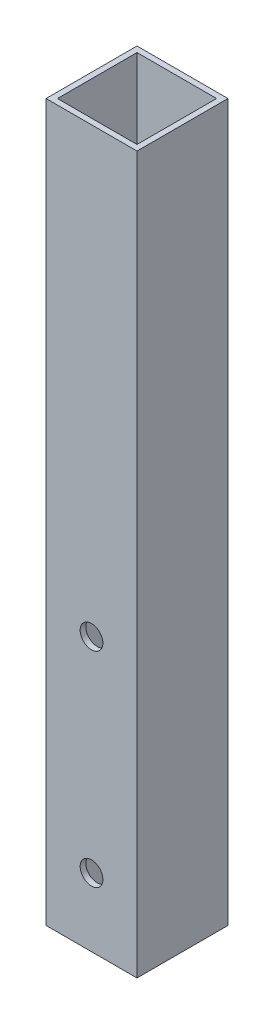
SolidWorks part; units mm, degrees
ref_plane "Front Plane" through (0, 0, 0) normal (0, 0, 1) x (1, 0, 0)
ref_plane "Top Plane" through (0, 0, 0) normal (0, 1, 0) x (1, 0, 0)
ref_plane "Right Plane" through (0, 0, 0) normal (1, 0, 0) x (0, 0, -1)
sketch "Sketch1" plane through (0, 0, 0) normal (0, 1, 0) x (1, 0, 0)
  line L1 (-11.1125, -11.1125) -> (11.1125, -11.1125)
  line L2 (-11.1125, -11.1125) -> (-11.1125, 11.1125)
  line L3 (-11.1125, 11.1125) -> (11.1125, 11.1125)
  line L4 (11.1125, -11.1125) -> (11.1125, 11.1125)
  line L5 (-11.1125, -11.1125) -> (11.1125, 11.1125) construction
  line L6 (-11.1125, 11.1125) -> (11.1125, -11.1125) construction
  line L7 (-12.7, -12.7) -> (12.7, -12.7)
  line L8 (-12.7, -12.7) -> (-12.7, 12.7)
  line L9 (-12.7, 12.7) -> (12.7, 12.7)
  line L10 (12.7, -12.7) -> (12.7, 12.7)
  line L11 (-12.7, -12.7) -> (12.7, 12.7) construction
  line L12 (-12.7, 12.7) -> (12.7, -12.7) construction
  point P0 (0, 0)
  point P6 (0, 0)
  dimension "D1" = 25.4
  dimension "D2" = 1.5875
extrude "Boss-Extrude1" add sketch "Sketch1" along normal blind 200
sketch "Sketch2" plane through (0, 0, -12.7) normal (0, 0, -1) x (-1, 0, 0)
  circle A0 centre (0, 76.2) radius 3.175
  circle A1 centre (0, 19.05) radius 3.175
  dimension "D3" = 6.35
  dimension "D1" = 57.15
  dimension "D2" = 19.05
extrude "Cut-Extrude1" cut sketch "Sketch2" against normal through all
